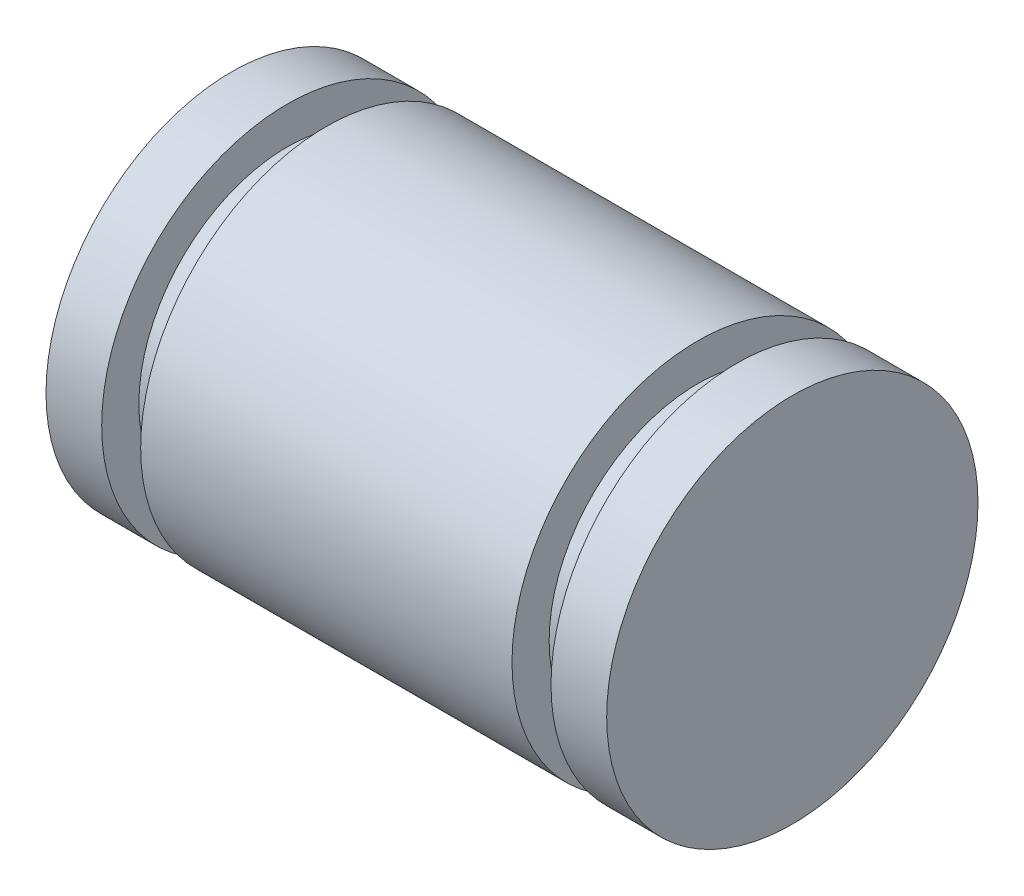
SolidWorks part; units mm, degrees
ref_plane "Front Plane" through (0, 0, 0) normal (0, 0, 1) x (1, 0, 0)
ref_plane "Top Plane" through (0, 0, 0) normal (0, 1, 0) x (1, 0, 0)
ref_plane "Right Plane" through (0, 0, 0) normal (1, 0, 0) x (0, 0, -1)
sketch "Sketch1" plane through (0, 0, 0) normal (0, 0, 1) x (1, 0, 0)
  line L0 (0, 0) -> (137.3217, 0) construction
  line L1 (0, -5) -> (1.5, -5)
  line L2 (0, 0) -> (0, -5)
  line L3 (1.5, -4) -> (1.5, -5)
  line L4 (2.55, -4) -> (2.55, -5)
  line L5 (1.5, -4) -> (2.55, -4)
  line L6 (0, -4) -> (137.3217, -4) construction
  line L7 (1.5, 0) -> (1.5, -5) construction
  line L8 (2.55, 0) -> (2.55, -5) construction
  line L9 (7.55, -5) -> (7.55, 9.3506) construction
  line L10 (0, -5) -> (137.3217, -5) construction
  line L11 (13.6, -4) -> (12.55, -4)
  line L12 (12.55, -4) -> (12.55, -5)
  line L13 (13.6, -4) -> (13.6, -5)
  line L14 (15.1, 0) -> (15.1, -5)
  line L15 (13.6, -5) -> (15.1, -5)
  line L16 (2.55, -5) -> (12.55, -5)
  line L17 (0, 0) -> (15.1, 0)
  dimension "D1" = 5
  dimension "D2" = 1.5
  dimension "D5" = 5
  dimension "D3" = 1.05
  dimension "D4" = 1
revolve "Revolve1" add sketch "Sketch1" angle 360 about L17
